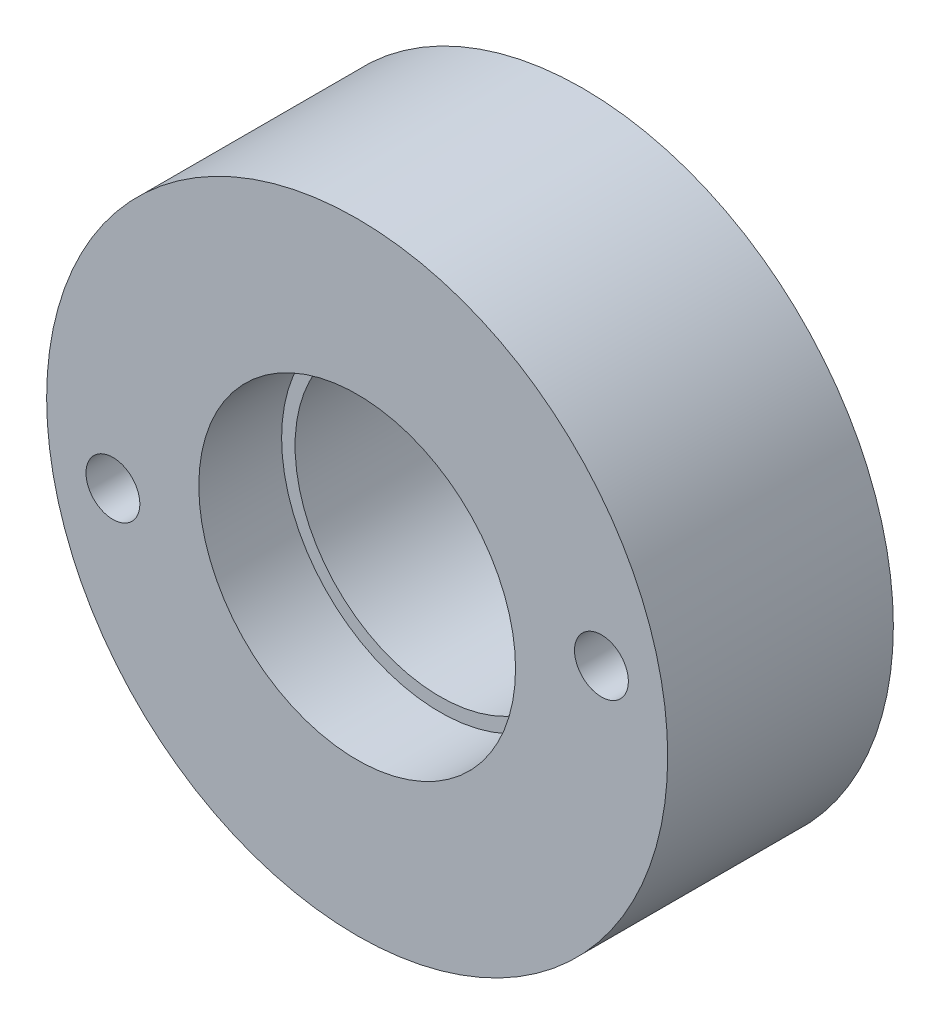
SolidWorks part; units mm, degrees
material "ナイロン"
ref_plane "正面" through (0, 0, 0) normal (0, 0, 1) x (1, 0, 0)
ref_plane "平面" through (0, 0, 0) normal (0, 1, 0) x (1, 0, 0)
ref_plane "右側面" through (0, 0, 0) normal (1, 0, 0) x (0, 0, -1)
sketch "ｽｹｯﾁ1" plane through (0, 0, 0) normal (0, 0, 1) x (1, 0, 0)
  circle A0 centre (0, 0) radius 7
  circle A1 centre (0, 0) radius 15
  dimension "D1" = 14
  dimension "D2" = 30
extrude "ﾎﾞｽ - 押し出し1" add sketch "ｽｹｯﾁ1" along normal blind 10.9
sketch "ｽｹｯﾁ2" plane through (0, 0, 0) normal (0, 0, -1) x (-1, 0, 0)
  line L0 (-14.7485, 2.7351) -> (14.7485, -2.7351) construction
  circle A0 centre (-11.7988, 2.1881) radius 1.3
  circle A1 centre (11.7988, -2.1881) radius 1.3
  circle A2 centre (0, 0) radius 15 construction
  dimension "D2" = 2.6
  dimension "D3" = 0
  dimension "D4" = 0
sketch "ｽｹｯﾁ5" plane through (0, 0, 10.9) normal (0, 0, 1) x (1, 0, 0)
  circle A0 centre (0, 0) radius 7.65
  dimension "D1" = 15.3
extrude "ｶｯﾄ - 押し出し3" cut sketch "ｽｹｯﾁ5" against normal blind 4
extrude "ｶｯﾄ - 押し出し4" cut sketch "ｽｹｯﾁ2" against normal through all
